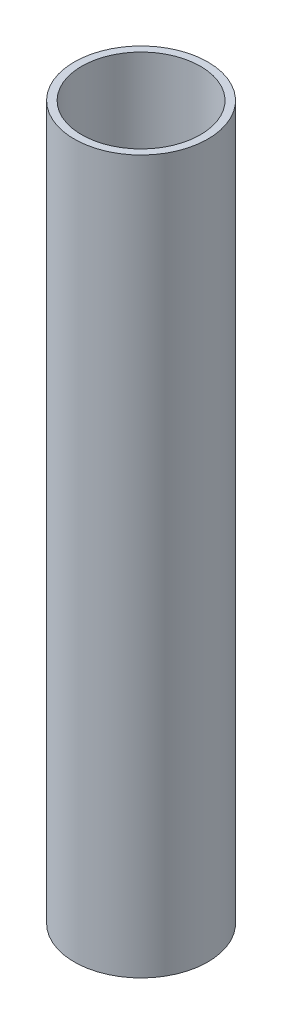
SolidWorks part; units mm, degrees
material "有机玻璃 (TM) GS 丙烯酸铸钣"
ref_plane "前视基准面" through (0, 0, 0) normal (0, 0, 1) x (1, 0, 0)
ref_plane "上视基准面" through (0, 0, 0) normal (0, 1, 0) x (1, 0, 0)
ref_plane "右视基准面" through (0, 0, 0) normal (1, 0, 0) x (0, 0, -1)
sketch "草图1" plane through (0, 0, 0) normal (0, 1, 0) x (1, 0, 0)
  circle A0 centre (0, 0) radius 50.8
  circle A1 centre (0, 0) radius 57.15
  dimension "D1" = 101.6
  dimension "D2" = 114.3
extrude "凸台-拉伸1" add sketch "草图1" along normal blind 609.6
